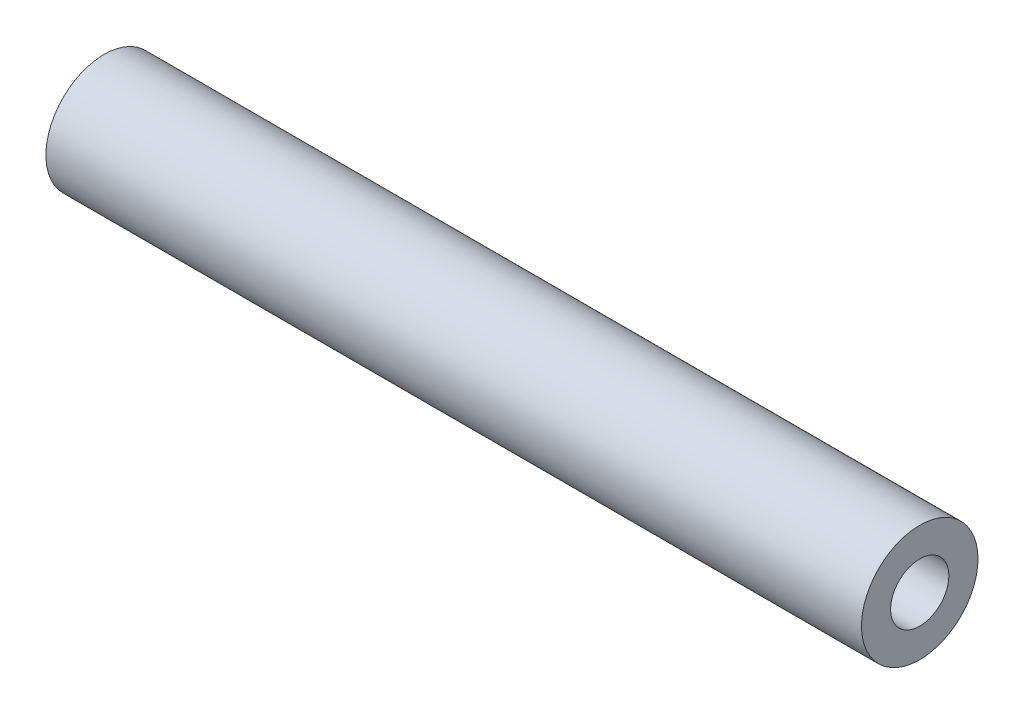
SolidWorks part; units mm, degrees
ref_plane "Front Plane" through (0, 0, 0) normal (0, 0, 1) x (1, 0, 0)
ref_plane "Top Plane" through (0, 0, 0) normal (0, 1, 0) x (1, 0, 0)
ref_plane "Right Plane" through (0, 0, 0) normal (1, 0, 0) x (0, 0, -1)
sketch "Sketch1" plane through (0, 0, 0) normal (1, 0, 0) x (0, 0, -1)
  circle A0 centre (0, 0) radius 12.7
  circle A1 centre (0, 0) radius 6.35
  dimension "D1" = 25.4
  dimension "D2" = 12.7
extrude "Boss-Extrude1" add sketch "Sketch1" along normal blind 177.8
